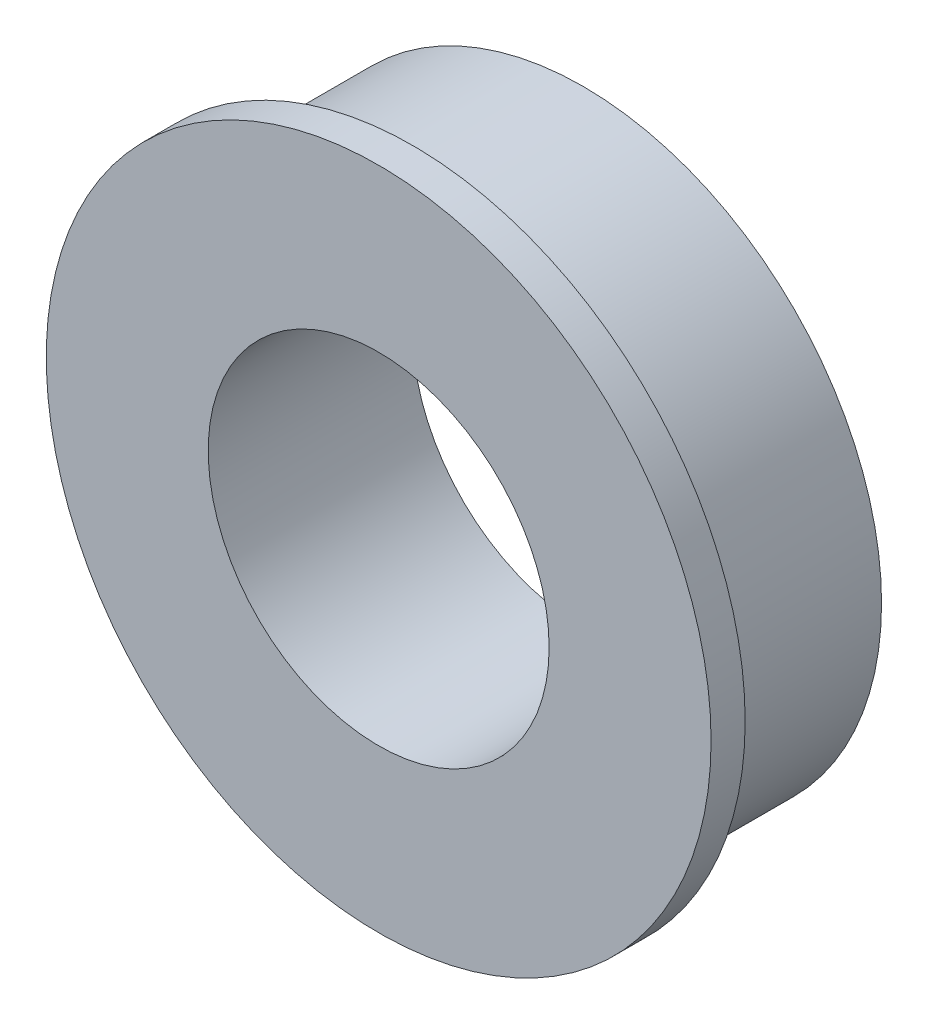
SolidWorks part; units mm, degrees
ref_plane "前视基准面" through (0, 0, 0) normal (0, 0, 1) x (1, 0, 0)
ref_plane "上视基准面" through (0, 0, 0) normal (0, 1, 0) x (1, 0, 0)
ref_plane "右视基准面" through (0, 0, 0) normal (1, 0, 0) x (0, 0, -1)
sketch "草图1" plane through (0, 0, 0) normal (0, 0, 1) x (1, 0, 0)
  circle A0 centre (0, 0) radius 4
  circle A1 centre (0, 0) radius 7
  dimension "D1" = 8
  dimension "D2" = 14
extrude "凸台-拉伸1" add sketch "草图1" along normal blind 4
sketch "草图2" plane through (0, 0, 4) normal (0, 0, 1) x (1, 0, 0)
  circle A0 centre (0, 0) radius 4
  circle A1 centre (0, 0) radius 7.8
  dimension "D1" = 15.6
extrude "凸台-拉伸2" add sketch "草图2" along normal blind 0.8
